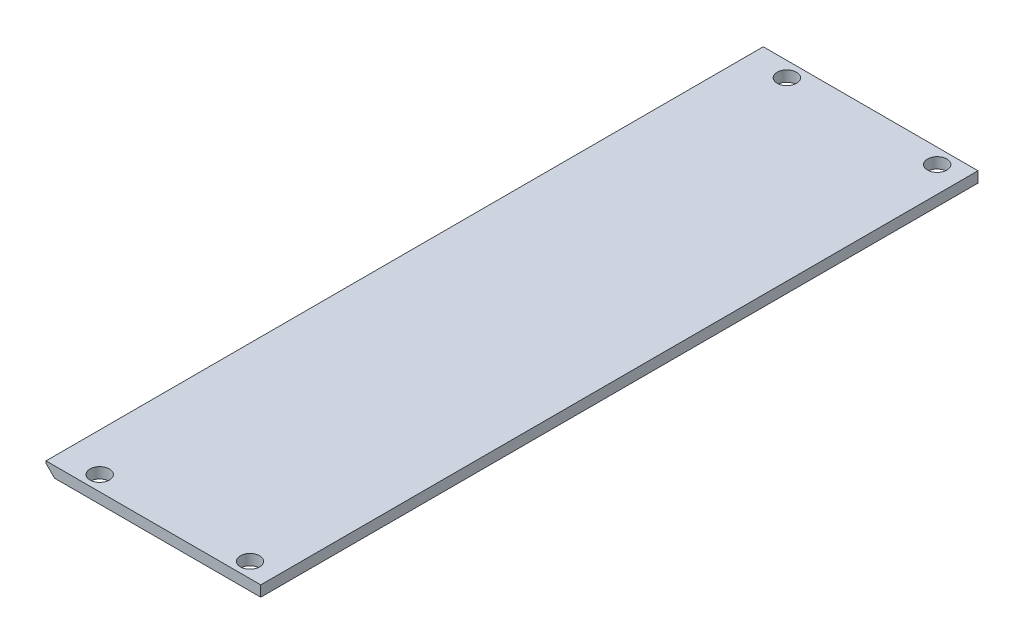
SolidWorks part; units mm, degrees
material "1.4301 (X5CrNi18-10)"
ref_plane "Vorne" through (0, 0, 0) normal (0, 0, 1) x (1, 0, 0)
ref_plane "Oben" through (0, 0, 0) normal (0, 1, 0) x (1, 0, 0)
ref_plane "Rechts" through (0, 0, 0) normal (1, 0, 0) x (0, 0, -1)
sketch "Skizze10" plane through (0, 0, 0) normal (0, 1, 0) x (1, 0, 0)
  line L1 (0, -167) -> (100, -167)
  line L2 (0, -167) -> (0, 167)
  line L3 (0, 167) -> (100, 167)
  line L4 (100, -167) -> (100, 167)
  point P4 (0, 0)
  dimension "D1" = 100
  dimension "D2" = 334
extrude "Aufsatz-Linear austragen1" add sketch "Skizze10" along normal blind 5
chamfer "Fase1" distance 4 angle 45 1 edges at (0, 0, 0)
hole_wizard "Durchgangsloch für M81" positions "Skizze13" profile "Skizze12" hole size "M8" standard "Gabler-Normteile" end condition through all
sketch "Skizze13" plane through (0, 5, 0) normal (0, 1, 0) x (1, 0, 0)
  line L0 (0, 0) -> (-42.2466, 0) construction
  line L1 (0, 167) -> (0, -167) construction
  line L3 (18, 160) -> (88, 160) construction
  line L5 (100, -167) -> (100, 167) construction
  point P0 (18, -160)
  point P2 (18, 160)
  point P11 (88, -160)
  point P14 (88, 160)
  dimension "D1" = 160
  dimension "D2" = 70
  dimension "D3" = 12
sketch "Skizze12" plane through (18, 5, 160) normal (1, 0, 0) x (0, 0, 1)
  line L0 (0, 0) -> (0, 5)
  line L1 (0, 5) -> (4.5, 5)
  line L2 (4.5, 5) -> (4.5, 0)
  line L5 (4.5, 0) -> (0, 0)
  line L11 (0, -6.35) -> (0, 107.95) construction
  dimension "Bohrerdurchmesser" = 9
  dimension "Bohrungstiefe" = 5
